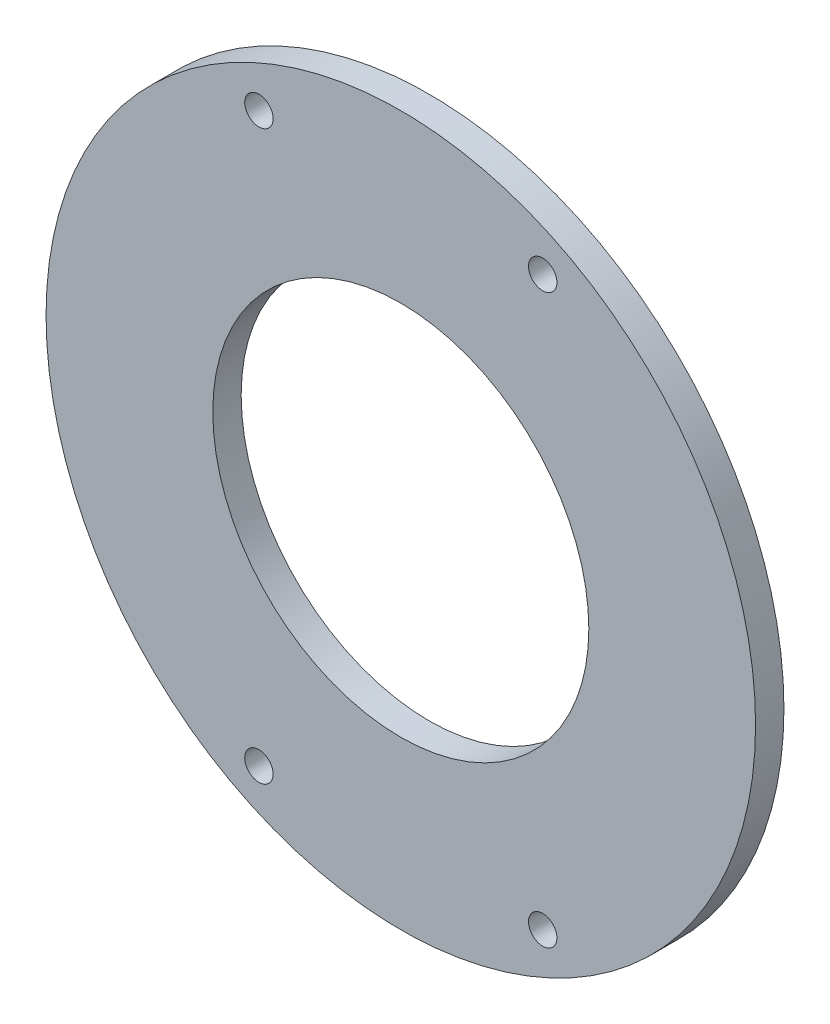
SolidWorks part; units mm, degrees
ref_plane "前视基准面" through (0, 0, 0) normal (0, 0, 1) x (1, 0, 0)
ref_plane "上视基准面" through (0, 0, 0) normal (0, 1, 0) x (1, 0, 0)
ref_plane "右视基准面" through (0, 0, 0) normal (1, 0, 0) x (0, 0, -1)
sketch "草图1" plane through (0, 0, 0) normal (0, 0, 1) x (1, 0, 0)
  line L0 (0, -1.8543) -> (0, -21.8543) construction
  line L1 (0, -21.8543) -> (-20, -21.8543) construction
  line L2 (0, -1.8543) -> (0, 64.1457) construction
  circle A0 centre (0, -1.8543) radius 10 construction
  circle A1 centre (0, -21.8543) radius 4.5 construction
  circle A2 centre (-20, -21.8543) radius 2 construction
  circle A3 centre (-20, 18.1457) radius 2
  circle A4 centre (20, 18.1457) radius 2
  circle A5 centre (20, -21.8543) radius 2 construction
  circle A6 centre (20, -61.8543) radius 2
  circle A7 centre (-20, -61.8543) radius 2
  circle A8 centre (0, -21.8543) radius 26.5
  circle A9 centre (0, -21.8543) radius 50
extrude "凸台-拉伸1" add sketch "草图1" along normal blind 4 contours A8
